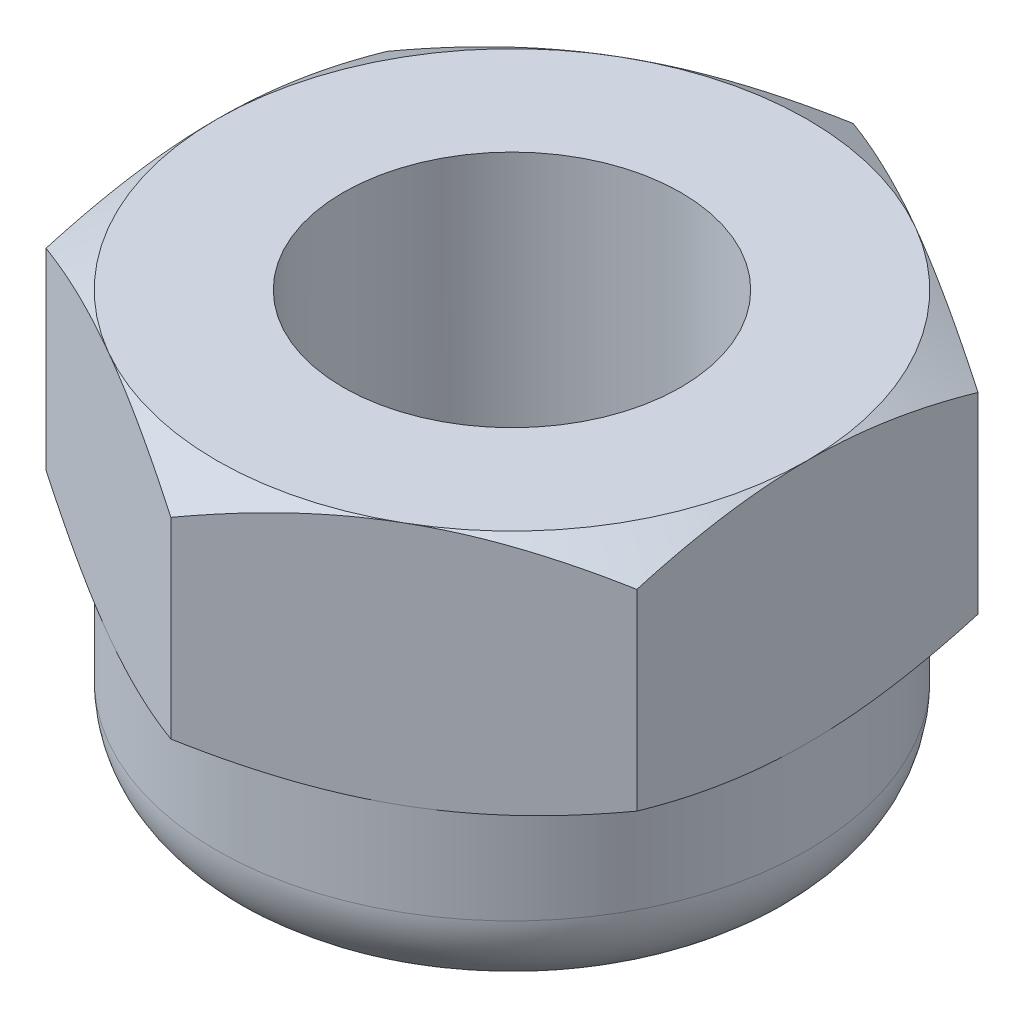
SolidWorks part; units mm, degrees
material "AISI 304"
ref_plane "前视基准面" through (0, 0, 0) normal (0, 0, 1) x (1, 0, 0)
ref_plane "上视基准面" through (0, 0, 0) normal (0, 1, 0) x (1, 0, 0)
ref_plane "右视基准面" through (0, 0, 0) normal (1, 0, 0) x (0, 0, -1)
sketch "草图1" plane through (0, 0, 0) normal (0, 1, 0) x (1, 0, 0)
  line L1 (3.5, 2.0207) -> (0, 4.0415)
  line L2 (0, 4.0415) -> (-3.5, 2.0207)
  line L3 (-3.5, 2.0207) -> (-3.5, -2.0207)
  line L4 (-3.5, -2.0207) -> (0, -4.0415)
  line L5 (0, -4.0415) -> (3.5, -2.0207)
  line L6 (3.5, -2.0207) -> (3.5, 2.0207)
  circle A0 centre (0, 0) radius 2
  circle A1 centre (0, 0) radius 3.5 construction
  dimension "D1" = 4
  dimension "D2" = 7
extrude "凸台-拉伸2" add sketch "草图1" along normal blind 2.9
cosmetic thread "装饰螺纹线1" parameters "D2"=22
sketch "草图2" plane through (0, 0, 0) normal (0, 0, 1) x (1, 0, 0)
  line L0 (3.5, 2.9) -> (6.0115, 2.9)
  line L1 (6.0115, 2.9) -> (6.0115, 1.45)
  line L2 (6.0115, 1.45) -> (3.5, 2.9)
  line L3 (3.5, 0) -> (6.0115, 0)
  line L4 (6.0115, 0) -> (6.0115, 1.45)
  line L5 (3.5, 0) -> (6.0115, 1.45)
  line L6 (0, 1.9814) -> (0, 2.9288) construction
  dimension "D1" = 30
  dimension "D2" = 30
revolve "切除-旋转1" cut sketch "草图2" angle 360 about L6
sketch "草图3" plane through (0, 0, 0) normal (0, -1, 0) x (1, 0, 0)
  circle A0 centre (0, 0) radius 3.5
  circle A1 centre (0, 0) radius 2
  dimension "D1" = 4
  dimension "D2" = 7
extrude "凸台-拉伸3" add sketch "草图3" along normal blind 2.1
fillet "圆角1" radius 1 1 edges at (0, -2.1, -3.5)
